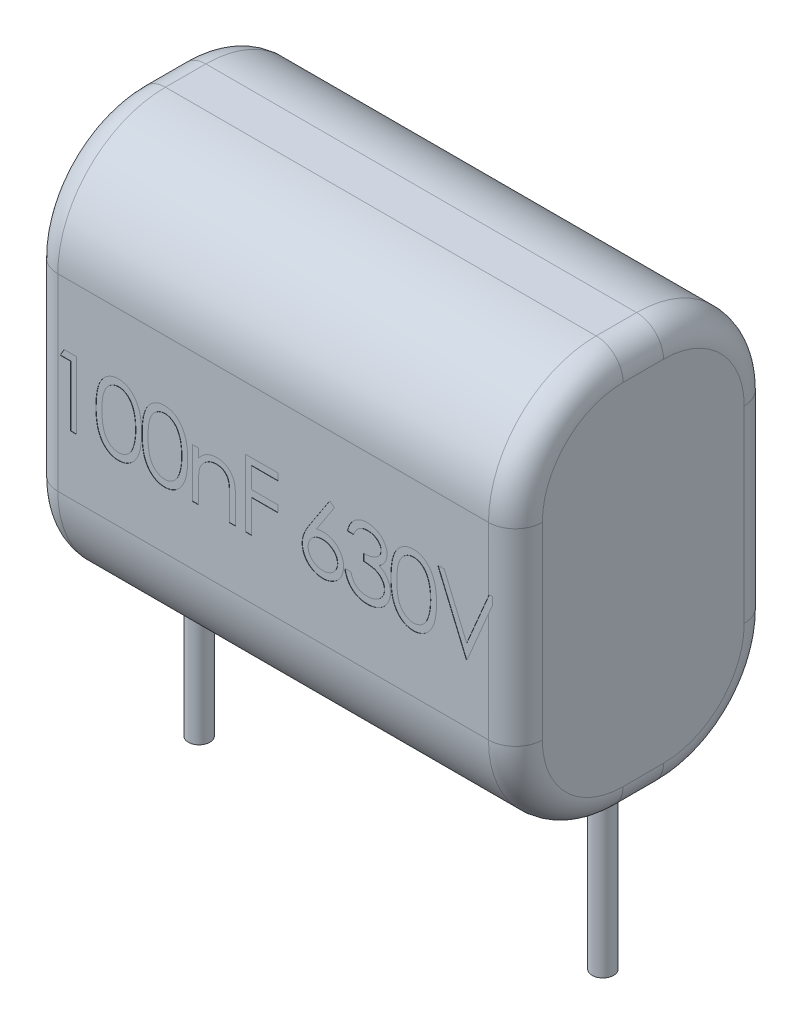
SolidWorks part; units mm, degrees
ref_plane "Front Plane" through (0, 0, 0) normal (0, 0, 1) x (1, 0, 0)
ref_plane "Top Plane" through (0, 0, 0) normal (0, 1, 0) x (1, 0, 0)
ref_plane "Right Plane" through (0, 0, 0) normal (1, 0, 0) x (0, 0, -1)
sketch "Sketch1" plane through (0, 0, 0) normal (1, 0, 0) x (0, 0, -1)
  line L1 (-0.75, 7.5) -> (0.75, 7.5)
  line L2 (-4.75, 3.5) -> (-4.75, -3.5)
  line L3 (-0.75, -7.5) -> (0.75, -7.5)
  line L4 (4.75, 3.5) -> (4.75, -3.5)
  line L5 (-4.75, 7.5) -> (4.75, -7.5) construction
  line L6 (-4.75, -7.5) -> (4.75, 7.5) construction
  arc A0 (4.75, -3.5) -> (0.75, -7.5) centre (0.75, -3.5) cw
  arc A1 (-0.75, -7.5) -> (-4.75, -3.5) centre (-0.75, -3.5) cw
  arc A2 (4.75, 3.5) -> (0.75, 7.5) centre (0.75, 3.5) ccw
  arc A3 (-4.75, 3.5) -> (-0.75, 7.5) centre (-0.75, 3.5) cw
  point P0 (0, 0)
  dimension "D3" = 4
  dimension "D1" = 15
  dimension "D2" = 9.5
extrude "Boss-Extrude1" add sketch "Sketch1" along normal mid plane 18
fillet "Fillet1" radius 1 16 edges at (-9, 0, -4.75) (-9, 6.3284, -3.5784) (-9, 7.5, 0) (-9, 6.3284, 3.5784) (-9, 0, 4.75) (-9, -6.3284, 3.5784) (-9, -7.5, 0) (-9, -6.3284, -3.5784) (9, -7.5, 0) (9, -6.3284, 3.5784) (9, 0, 4.75) (9, 6.3284, 3.5784) (9, 7.5, 0) (9, 6.3284, -3.5784) (9, 0, -4.75) (9, -6.3284, -3.5784)
sketch "Sketch2" plane through (0, 0, 0) normal (0, 1, 0) x (1, 0, 0)
  line L0 (0, 7.3846) -> (0, -6.8387) construction
  circle A0 centre (7.5, 0) radius 0.4
  circle A1 centre (-7.5, 0) radius 0.4
  dimension "D1" = 0.8
  dimension "D2" = 15
extrude "Boss-Extrude2" add sketch "Sketch2" against normal blind 13.5
sketch "Sketch4" plane through (0, 0, 4.75) normal (0, 0, 1) x (1, 0, 0)
  line L0 (-9, -1.3204) -> (9, -1.3204) construction
  line L1 (-9, -3.5) -> (-9, 3.5) construction
  line L2 (9, 3.5) -> (9, -3.5) construction
  text T0 "100nF 630V" font "Century Gothic" height 2.5
  point P3 (-9, -1.8243)
  point P6 (9, -2.0162)
  point P9 (-9, -1.3204)
extrude "Cut-Extrude1" cut sketch "Sketch4" against normal blind 0.01
